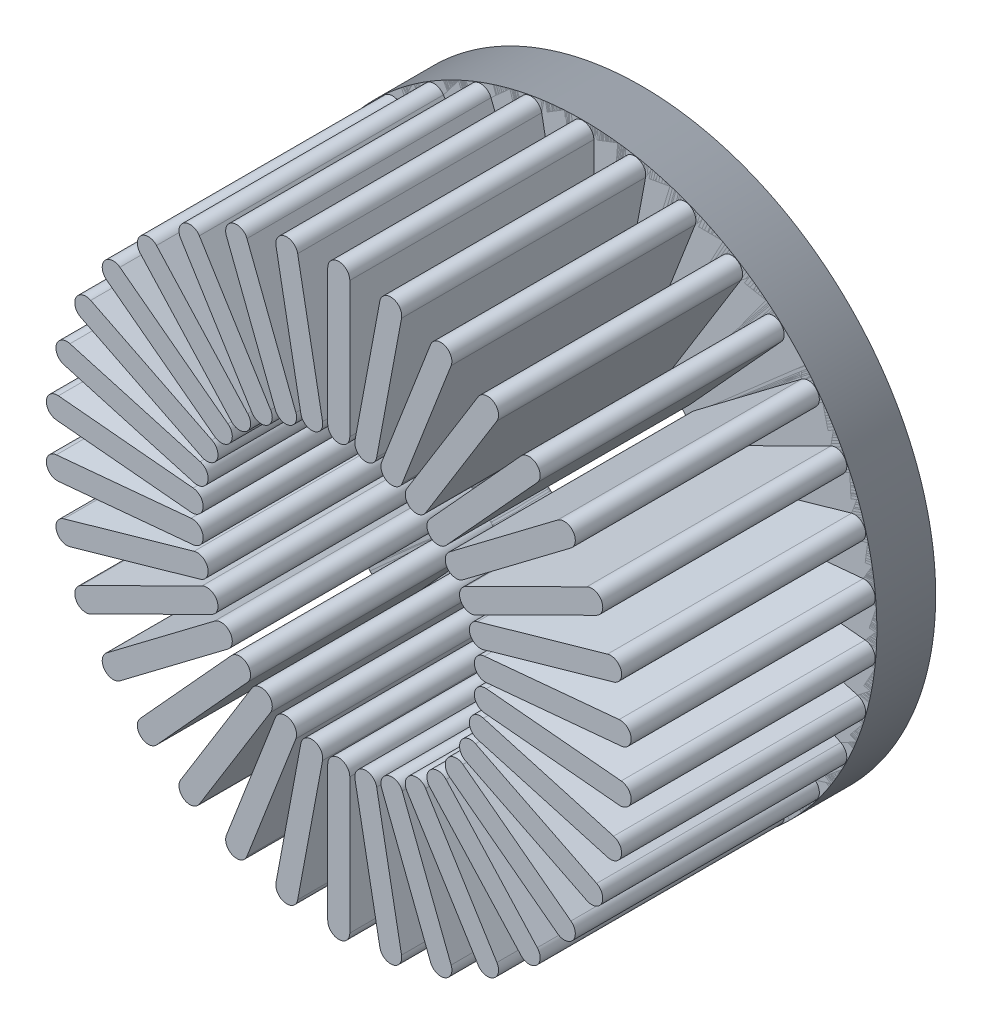
SolidWorks part; units mm, degrees
ref_plane "Front Plane" through (0, 0, 0) normal (0, 0, 1) x (1, 0, 0)
ref_plane "Top Plane" through (0, 0, 0) normal (0, 1, 0) x (1, 0, 0)
ref_plane "Right Plane" through (0, 0, 0) normal (1, 0, 0) x (0, 0, -1)
sketch "Sketch2" plane through (0, 0, 0) normal (0, 0, 1) x (1, 0, 0)
  circle A0 centre (0, 0) radius 20
  circle A1 centre (0, 0) radius 9.3
  dimension "D1" = 40
  dimension "D2" = 18.6
extrude "Boss-Extrude1" add sketch "Sketch2" along normal blind 4
sketch "Sketch3" plane through (0, 0, 4) normal (0, 0, 1) x (1, 0, 0)
  line L0 (0, 19.2221) -> (0, 10.0161) construction
  line L1 (0.75, 19.2221) -> (0.75, 10.0161)
  line L2 (-0.75, 19.2221) -> (-0.75, 10.0161)
  arc A0 (0.75, 19.2221) -> (-0.75, 19.2221) centre (0, 19.2221) ccw
  arc A1 (-0.75, 10.0161) -> (0.75, 10.0161) centre (0, 10.0161) ccw
  point P2 (0, 14.6191)
extrude "Boss-Extrude2" add sketch "Sketch3" along normal blind 16.6
pattern_circular "CirPattern1" count 34 over 360 about axis through (0, 0, 0) along (0, 0, 1) of bodies 139
